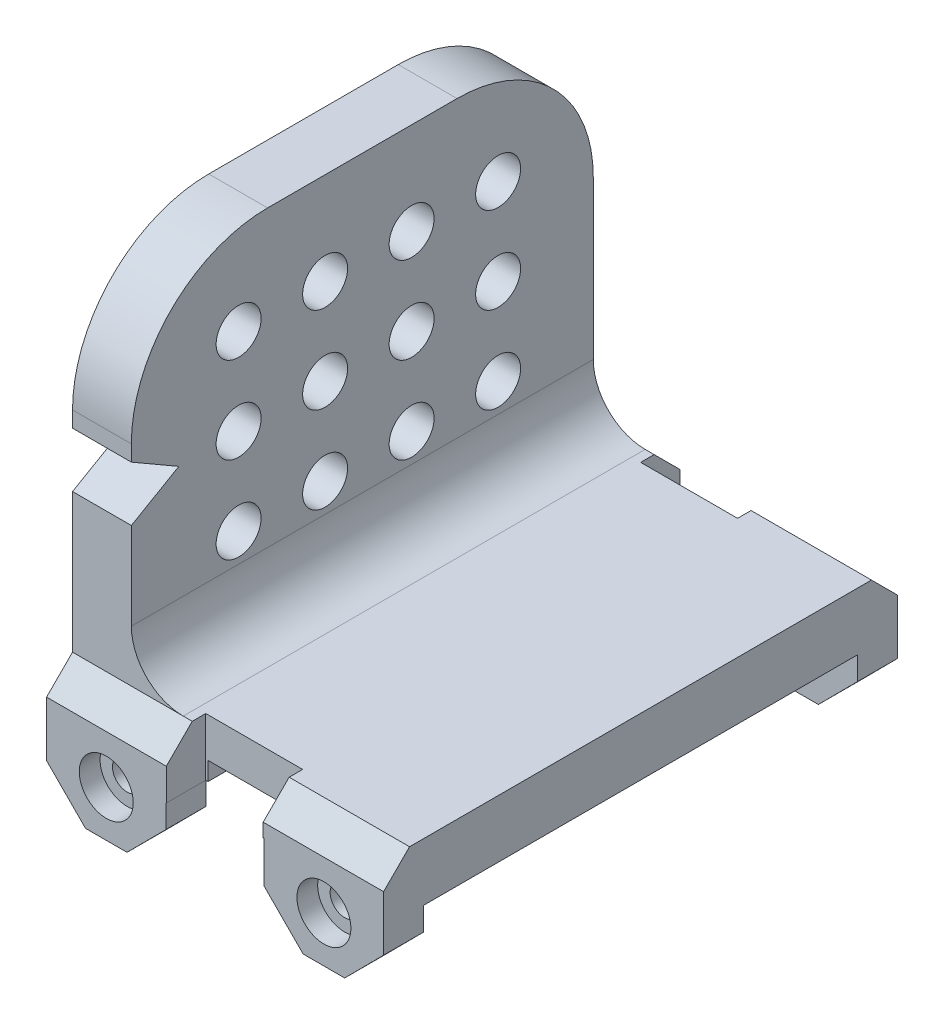
SolidWorks part; units mm, degrees
ref_plane "Front Plane" through (0, 0, 0) normal (0, 0, 1) x (1, 0, 0)
ref_plane "Top Plane" through (0, 0, 0) normal (0, 1, 0) x (1, 0, 0)
ref_plane "Right Plane" through (0, 0, 0) normal (1, 0, 0) x (0, 0, -1)
sketch "Sketch1" plane through (0, 0, 0) normal (0, 1, 0) x (1, 0, 0)
  line L1 (-12.3698, 18.8595) -> (12.3698, 18.8595)
  line L2 (-12.3698, 18.8595) -> (-12.3698, -18.8595)
  line L3 (-12.3698, -18.8595) -> (12.3698, -18.8595)
  line L4 (12.3698, 18.8595) -> (12.3698, -18.8595)
  line L6 (-55, 0) -> (55, 0) construction
  line L7 (0, -55) -> (0, 55) construction
  point P4 (0, 0)
  point P5 (0, 0)
  point P6 (0, 0)
  point P7 (0, 0)
  point P8 (0, 0)
  point P9 (0, 0)
  point P11 (0, 0)
  point P13 (12.3698, 0)
  point P14 (0, 18.8595)
extrude "Boss-Extrude1" add sketch "Sketch1" along normal blind 4.2418
sketch "Sketch2" plane through (0, 0, -18.8595) normal (0, 0, -1) x (-1, 0, 0)
  line L6 (-12.3698, -1.7018) -> (-12.3698, 4.2418)
  line L7 (-12.3698, 4.2418) -> (-3.6068, 4.2418)
  line L8 (-12.3698, 4.2418) -> (12.3698, 4.2418) construction
  line L9 (-3.6068, 4.2418) -> (-3.6068, -1.7018)
  line L10 (-7.9883, 4.2418) -> (-7.9883, -4.5797) construction
  line L11 (-9.5123, -4.5797) -> (-6.4643, -4.5797)
  line L14 (-12.3698, -1.7018) -> (-9.5123, -4.5797)
  line L15 (-3.6068, -1.7018) -> (-6.4643, -4.5797)
  point P12 (-7.9883, -4.5797)
extrude "Boss-Extrude2" add sketch "Sketch2" against normal blind 2.9464
mirror "Mirror1" about plane through (0, 0, 0) normal (1, 0, 0) of "Boss-Extrude2"
mirror "Mirror2" about plane through (0, 0, 0) normal (0, 0, 1) of "Mirror1", "Boss-Extrude2"
sketch "Sketch3" plane through (0, 0, 0) normal (0, -1, 0) x (1, 0, 0)
  line L0 (-3.6068, 15.9131) -> (-12.3698, 15.9131) construction
  line L1 (-11.3538, 15.9131) -> (-4.3688, 15.9131)
  line L2 (-11.3538, 15.9131) -> (-11.3538, -15.9131)
  line L3 (-11.3538, -15.9131) -> (-4.3688, -15.9131)
  line L4 (-4.3688, 15.9131) -> (-4.3688, -15.9131)
  line L5 (-12.3698, -15.9131) -> (-3.6068, -15.9131) construction
  line L6 (-12.3698, 15.9131) -> (-11.3538, 15.9131) construction
extrude "Cut-Extrude1" cut sketch "Sketch3" against normal blind 1.3462
pattern_linear "LPattern1" count 3 spacing 7.9502 along (1, 0, 0) of "Cut-Extrude1"
sketch "Sketch4" plane through (0, 0, -18.8595) normal (0, 0, -1) x (-1, 0, 0)
  line L0 (-7.9883, -4.5797) -> (-7.9883, -1.2015) construction
  line L1 (-9.5123, -4.5797) -> (-6.4643, -4.5797) construction
  circle A0 centre (-7.9883, -1.2015) radius 1.0668
extrude "Cut-Extrude2" cut sketch "Sketch4" against normal through all both and the other way through all
mirror "Mirror3" about plane through (0, 0, 0) normal (1, 0, 0) of "Cut-Extrude2"
sketch "Sketch5" plane through (0, 0, -18.8595) normal (0, 0, -1) x (-1, 0, 0)
  circle A0 centre (-7.9883, -1.2015) radius 1.9812
extrude "Cut-Extrude3" cut sketch "Sketch5" against normal blind 1.524
mirror "Mirror4" about plane through (0, 0, 0) normal (0, 0, 1) of "Cut-Extrude3" second plane through (0, 0, 0) second plane normal (1, 0, 0)
sketch "Sketch6" plane through (0, 4.2418, 0) normal (0, 1, 0) x (1, 0, 0)
  line L0 (-12.3698, 18.8595) -> (-3.5814, 18.8595) construction
  line L1 (12.3698, 18.8595) -> (-12.3698, 18.8595) construction
  line L3 (-3.5814, 18.8595) -> (3.5306, 18.8595)
  line L4 (-3.5814, 18.8595) -> (-3.5814, 15.9639)
  line L5 (-3.5814, 15.9639) -> (3.5306, 15.9639)
  line L6 (3.5306, 18.8595) -> (3.5306, 15.9639)
extrude "Cut-Extrude4" cut sketch "Sketch6" against normal through all
mirror "Mirror5" about plane through (0, 0, 0) normal (0, 0, 1) of "Cut-Extrude4"
sketch "Sketch7" plane through (0, 0, 15.9131) normal (0, 0, -1) x (-1, 0, 0)
  line L1 (3.4102, 1.3447) -> (-3.5771, 1.3447)
  line L2 (3.4102, 1.3447) -> (3.4102, 0)
  line L3 (3.4102, 0) -> (-3.5771, 0)
  line L4 (-3.5771, 1.3447) -> (-3.5771, 0)
  point P4 (0, 0)
  point P8 (-3.5306, 0)
  point P9 (0, 0)
extrude "Cut-Extrude5" cut sketch "Sketch7" against normal mid plane 127
chamfer "Chamfer2" distance 1.905 angle 45 2 edges at (7.9502, 4.2418, -18.8595) (-7.9756, 4.2418, 18.8595)
sketch "Sketch8" plane through (0, 4.2418, 0) normal (0, 1, 0) x (1, 0, 0)
  line L0 (-12.3698, -16.9545) -> (-3.5814, -16.9545) construction
  line L1 (-12.3698, 16.9545) -> (-8.0518, 16.9545)
  line L2 (-12.3698, 16.9545) -> (-12.3698, -16.9545)
  line L3 (-12.3698, -16.9545) -> (-8.0518, -16.9545)
  line L4 (-8.0518, 16.9545) -> (-8.0518, -16.9545)
extrude "Boss-Extrude3" add sketch "Sketch8" along normal blind 25.4
sketch "Sketch9" plane through (-8.0518, 0, 0) normal (1, 0, 0) x (0, 0, -1)
  line L0 (9.9695, 0) -> (9.9695, 16.51) construction
  line L1 (13.6068, 0) -> (-13.6068, 0) construction
  line L2 (9.9695, 16.51) -> (18.8595, 16.51) construction
  line L6 (18.8595, 0.3175) -> (18.8595, 19.9389) construction
  line L7 (18.8595, 2.3368) -> (18.8595, -1.7018) construction
  circle A0 centre (9.9695, 16.51) radius 1.651
extrude "Cut-Extrude6" cut sketch "Sketch9" against normal blind 25.4
fillet "Fillet1" radius 10 2 edges at (-10.2108, 29.6418, -16.9545) (-10.2108, 29.6418, 16.9545)
fillet "Fillet2" radius 3.81 1 edges at (-8.0518, 4.2418, 0)
pattern_linear "LPattern4" count 2 spacing 6.35 along (0, -1, 0) count 4 spacing 6.35 along (0, 0, 1) of "Cut-Extrude6"
pattern_linear "LPattern5" count 2 spacing 6.35 along (0, 1, 0) of "LPattern4", "Cut-Extrude6"
sketch "Sketch10" plane through (-12.3698, 0, 0) normal (-1, 0, 0) x (0, 0, 1)
  line L0 (16.9545, 18.4798) -> (13.4678, 16.4668)
  line L1 (16.9545, 19.6418) -> (16.9545, 4.2418) construction
  line L2 (13.4678, 16.4668) -> (16.9545, 14.4537)
  line L3 (16.9545, 14.4537) -> (16.9545, 18.4798)
extrude "Cut-Extrude7" cut sketch "Sketch10" against normal blind 25.4
